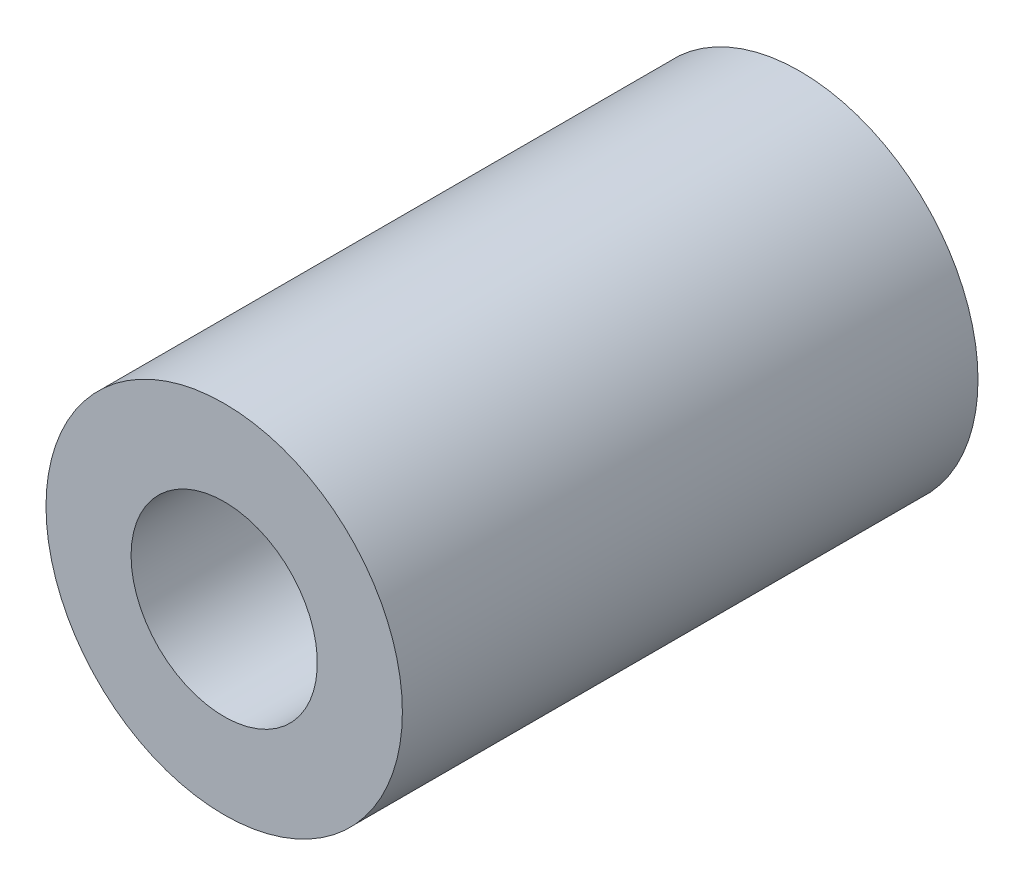
SolidWorks part; units mm, degrees
ref_plane "Front Plane" through (0, 0, 0) normal (0, 0, 1) x (1, 0, 0)
ref_plane "Top Plane" through (0, 0, 0) normal (0, 1, 0) x (1, 0, 0)
ref_plane "Right Plane" through (0, 0, 0) normal (1, 0, 0) x (0, 0, -1)
sketch "Sketch1" plane through (0, 0, 0) normal (0, 0, 1) x (1, 0, 0)
  circle A0 centre (0, 0) radius 2.4892
  circle A1 centre (0, 0) radius 4.7625
  dimension "D1" = 4.9784
  dimension "D2" = 9.525
extrude "Boss-Extrude1" add sketch "Sketch1" along normal mid plane 15.3848 contours A0 | A1
